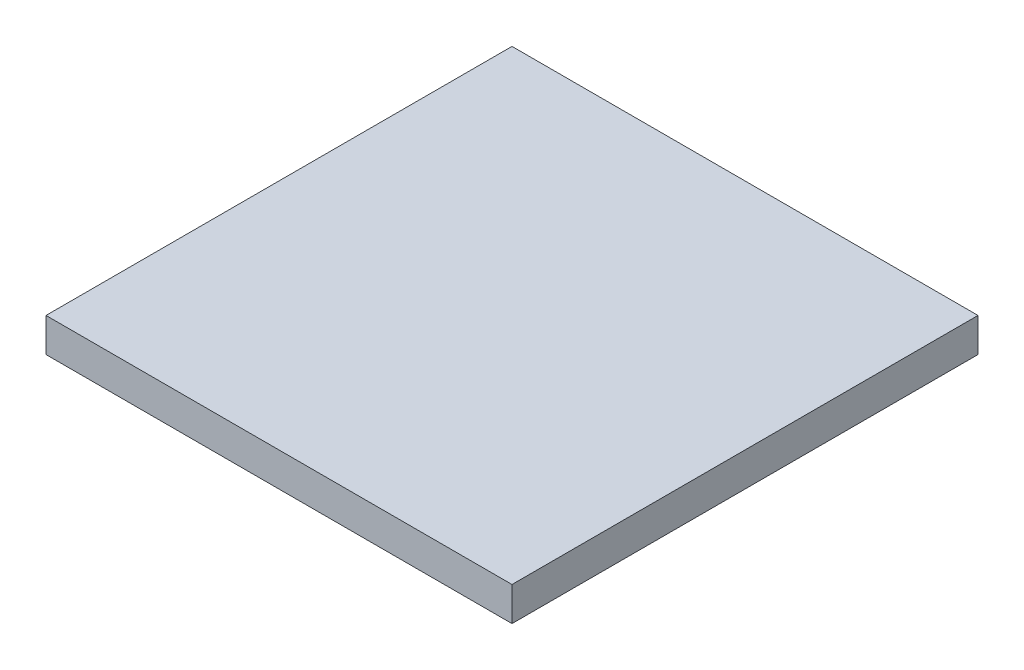
SolidWorks part; units mm, degrees
material "Galvanized Steel"
ref_plane "Front Plane" through (0, 0, 0) normal (0, 0, 1) x (1, 0, 0)
ref_plane "Top Plane" through (0, 0, 0) normal (0, 1, 0) x (1, 0, 0)
ref_plane "Right Plane" through (0, 0, 0) normal (1, 0, 0) x (0, 0, -1)
sketch "Sketch1" plane through (0, 0, 0) normal (0, 1, 0) x (1, 0, 0)
  line L1 (-13.75, 13.75) -> (13.75, 13.75)
  line L2 (-13.75, 13.75) -> (-13.75, -13.75)
  line L3 (-13.75, -13.75) -> (13.75, -13.75)
  line L4 (13.75, 13.75) -> (13.75, -13.75)
  line L5 (-13.75, 13.75) -> (13.75, -13.75) construction
  line L6 (-13.75, -13.75) -> (13.75, 13.75) construction
  point P0 (0, 0)
extrude "Boss-Extrude1" add sketch "Sketch1" along normal blind 2
